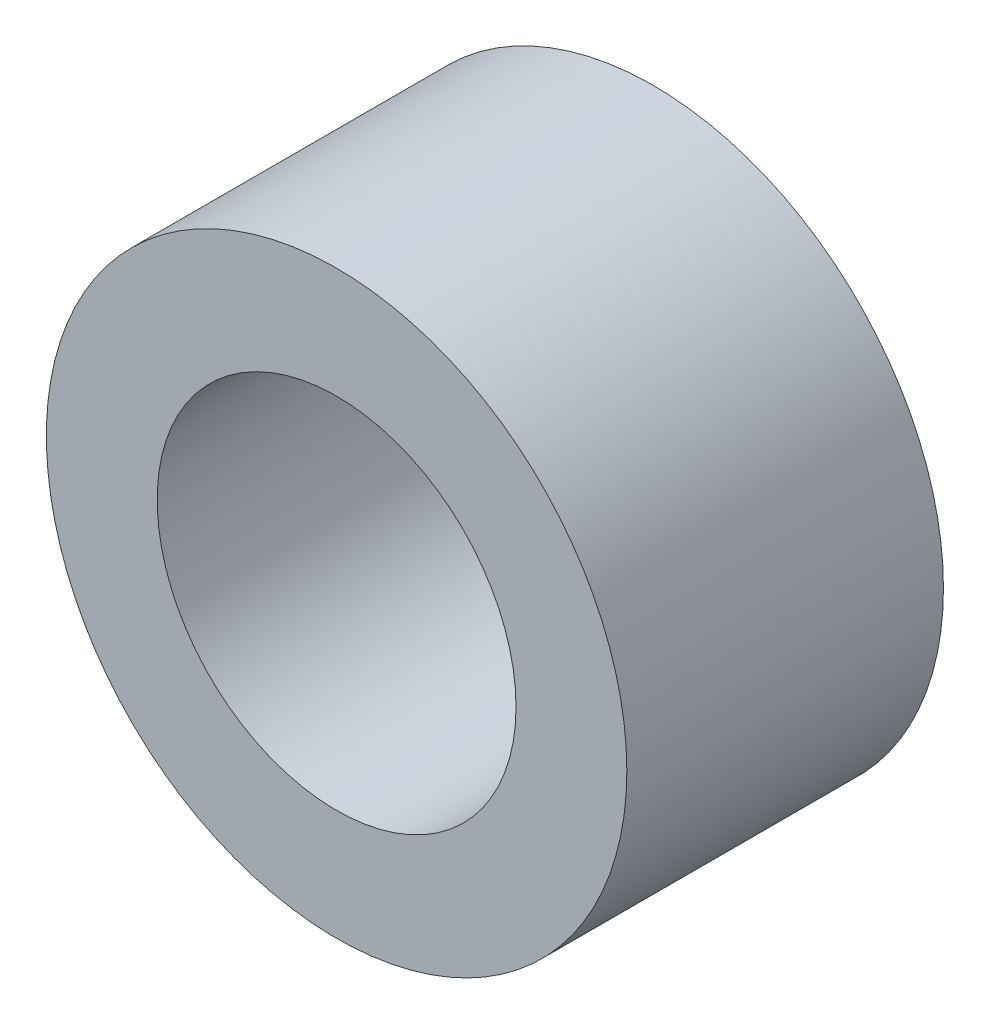
SolidWorks part; units mm, degrees
ref_plane "Plan de face" through (0, 0, 0) normal (0, 0, 1) x (1, 0, 0)
ref_plane "Plan de dessus" through (0, 0, 0) normal (0, 1, 0) x (1, 0, 0)
ref_plane "Plan de droite" through (0, 0, 0) normal (1, 0, 0) x (0, 0, -1)
sketch "Esquisse1" plane through (0, 0, 0) normal (0, 0, 1) x (1, 0, 0)
  circle A0 centre (0, 0) radius 3.4
  circle A1 centre (0, 0) radius 5.5
  dimension "D1" = 6.8
  dimension "D2" = 11
extrude "Boss.-Extru.1" add sketch "Esquisse1" along normal blind 6
